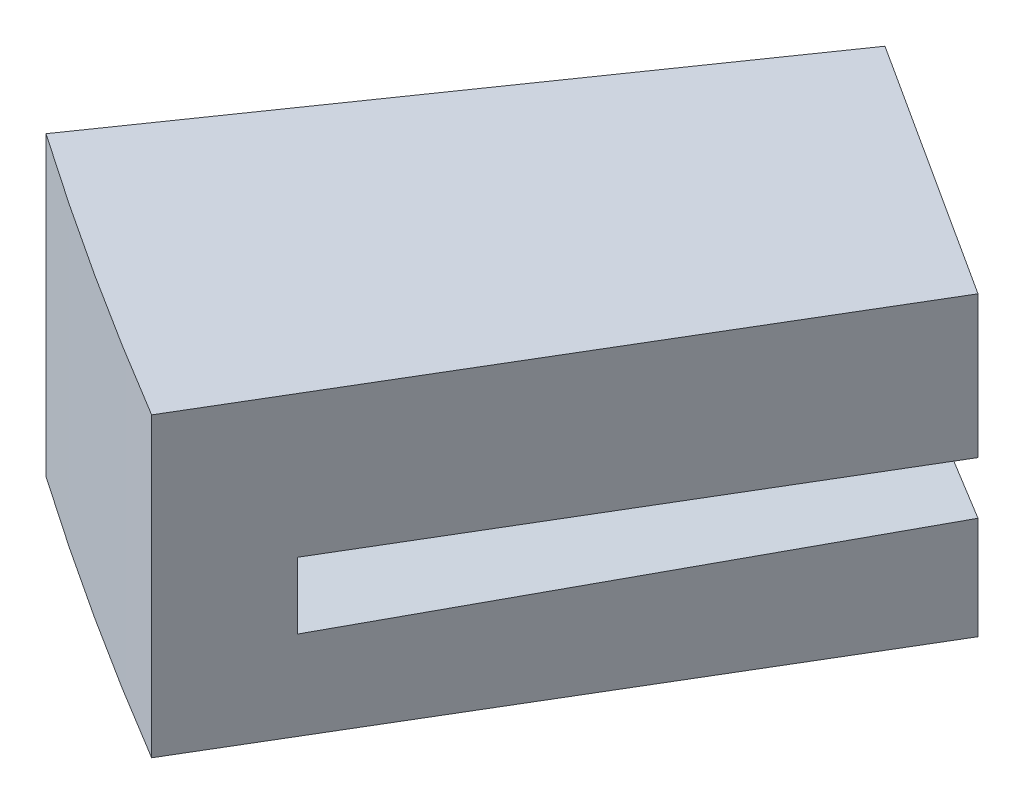
SolidWorks part; units mm, degrees
ref_plane "Front Plane" through (0, 0, 0) normal (0, 0, 1) x (1, 0, 0)
ref_plane "Top Plane" through (0, 0, 0) normal (0, 1, 0) x (1, 0, 0)
ref_plane "Right Plane" through (0, 0, 0) normal (1, 0, 0) x (0, 0, -1)
sketch "Sketch1" plane through (0, 0, 0) normal (0, 1, 0) x (1, 0, 0)
  line L2 (-201.8325, -290.8258) -> (-206.177, -297.0859)
  line L3 (-181.0539, -304.1965) -> (-184.9511, -310.7444)
  arc A0 (-201.8325, -290.8258) -> (-181.0539, -304.1965) centre (0, 0) ccw
  arc A1 (-206.177, -297.0859) -> (-184.9511, -310.7444) centre (0, 0) ccw
  dimension "D1" = 354
  dimension "D2" = 4
  dimension "D3" = 7.62
  dimension "D4" = 7.62
extrude "Boss-Extrude1" add sketch "Sketch1" along normal blind 4.7625
sketch "Sketch2" plane through (0, 4.7625, 0) normal (0, 1, 0) x (1, 0, 0)
  line L0 (-206.177, -297.0859) -> (-181.558, -261.6118)
  line L1 (-184.9511, -310.7444) -> (-162.8666, -273.6393)
  line L2 (-181.558, -261.6118) -> (-162.8666, -273.6393)
  arc A0 (-206.177, -297.0859) -> (-184.9511, -310.7444) centre (0, 0) ccw
  dimension "D1" = 35.56
  dimension "D2" = 35.56
extrude "Boss-Extrude2" add sketch "Sketch2" along normal blind 10.16
sketch "Sketch3" plane through (0, 0, 0) normal (0, -1, 0) x (1, 0, 0)
  line L0 (-184.9511, 310.7444) -> (-162.8666, 273.6393)
  line L1 (-206.177, 297.0859) -> (-181.558, 261.6118)
  line L2 (-162.8666, 273.6393) -> (-181.558, 261.6118)
  arc A0 (-206.177, 297.0859) -> (-184.9511, 310.7444) centre (0, 0) cw
  arc A1 (-184.9511, 310.7444) -> (-206.177, 297.0859) centre (0, 0) ccw construction
  line M1 (-206.177, 297.0859) -> (-201.8325, 290.8258)
  arc M2 (-201.8325, 290.8258) -> (-181.0539, 304.1965) centre (0, 0) cw
  line M3 (-181.0539, 304.1965) -> (-184.9511, 310.7444)
  arc M4 (-184.9511, 310.7444) -> (-206.177, 297.0859) centre (0, 0) ccw
  dimension "D1" = 35.56
  dimension "D2" = 35.56
extrude "Boss-Extrude3" add sketch "Sketch3" along normal blind 6.35 contours M4 M1 M2 M3 | L2 L0 L1 M2
sketch "Sketch4" plane through (0, 0, 0) normal (-0.8215, 0, -0.5701) x (-0.5701, 0, 0.8215)
  line L0 (354, 0) -> (318.44, 0)
  line L1 (318.44, 0) -> (318.44, 1)
  line L2 (318.44, 1) -> (354, 0)
  dimension "D1" = 1
sketch "Sketch5" plane through (0, 0, 0) normal (-0.8215, 0, -0.5701) x (-0.5701, 0, 0.8215)
  line L0 (0, 0) -> (0, 142.9973)
revolve "Revolve1" add sketch "Sketch4" angle 4 about L0
